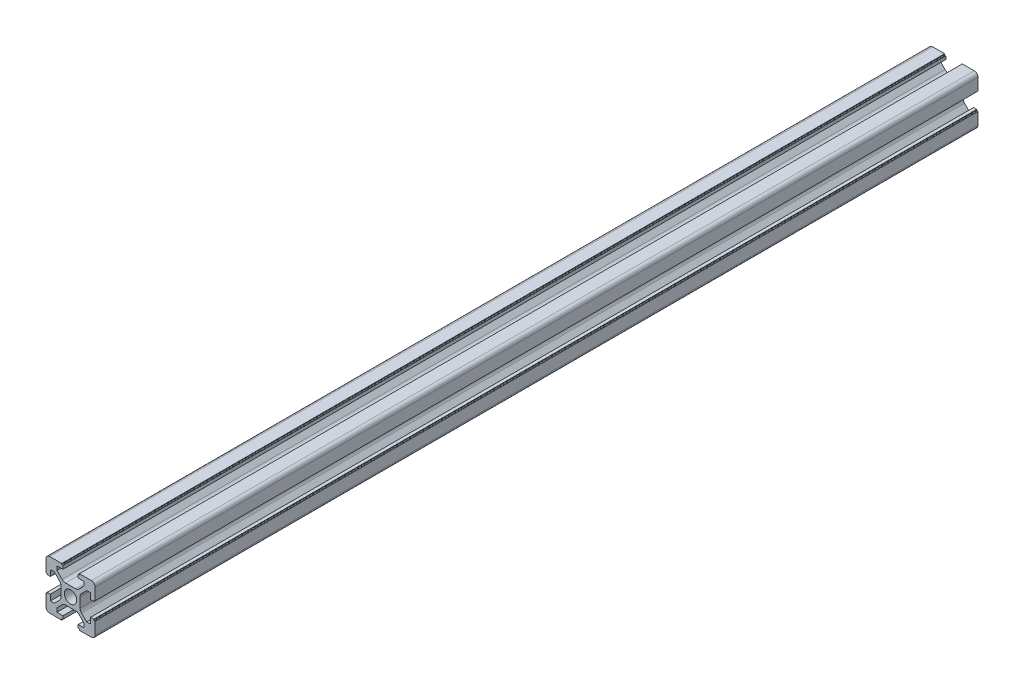
SolidWorks part; units mm, degrees
material "6063-T6"
ref_plane "Спереди" through (0, 0, 0) normal (0, 0, 1) x (1, 0, 0)
ref_plane "Сверху" through (0, 0, 0) normal (0, 1, 0) x (1, 0, 0)
ref_plane "Справа" through (0, 0, 0) normal (1, 0, 0) x (0, 0, -1)
sketch "Sketch1" plane through (0, 0, 0) normal (0, 0, 1) x (1, 0, 0)
  line L0 (0, 10) -> (0, -10) construction
  line L1 (-10, -10) -> (10, -10) construction
  line L2 (-10, -10) -> (-10, 10) construction
  line L3 (-10, 10) -> (10, 10) construction
  line L4 (10, -10) -> (10, 10) construction
  line L5 (-10, -10) -> (10, 10) construction
  line L6 (-10, 10) -> (10, -10) construction
  line L7 (-10, 0) -> (10, 0) construction
  line L8 (0, 3.9) -> (-2.0109, 3.9)
  line L9 (-3.4251, 4.4858) -> (-5.5393, 6.6)
  line L10 (-5.5393, 6.6) -> (-5.5393, 8.2)
  line L11 (-5.5393, 8.2) -> (-3.1, 8.2)
  line L12 (-3.1, 8.2) -> (-3.1, 9.5)
  line L13 (-3.1, 9.5) -> (-3.4, 9.5)
  line L14 (-3.6, 9.7) -> (-3.6, 10)
  line L15 (-3.6, 10) -> (-8.5, 10)
  line L16 (-10, 3.6) -> (-10, 8.5)
  line L17 (-9.7, 3.6) -> (-10, 3.6)
  line L18 (-9.5, 3.1) -> (-9.5, 3.4)
  line L19 (-8.2, 3.1) -> (-9.5, 3.1)
  line L20 (-8.2, 5.5393) -> (-8.2, 3.1)
  line L21 (-6.6, 5.5393) -> (-8.2, 5.5393)
  line L22 (-4.4858, 3.4251) -> (-6.6, 5.5393)
  line L23 (-3.9, 0) -> (-3.9, 2.0109)
  line L24 (3.9, 0) -> (3.9, 2.0109)
  line L25 (4.4858, 3.4251) -> (6.6, 5.5393)
  line L26 (6.6, 5.5393) -> (8.2, 5.5393)
  line L27 (8.2, 5.5393) -> (8.2, 3.1)
  line L28 (8.2, 3.1) -> (9.5, 3.1)
  line L29 (9.5, 3.1) -> (9.5, 3.4)
  line L30 (9.7, 3.6) -> (10, 3.6)
  line L31 (10, 3.6) -> (10, 8.5)
  line L32 (3.6, 10) -> (8.5, 10)
  line L33 (3.6, 9.7) -> (3.6, 10)
  line L34 (3.1, 9.5) -> (3.4, 9.5)
  line L35 (3.1, 8.2) -> (3.1, 9.5)
  line L36 (5.5393, 8.2) -> (3.1, 8.2)
  line L37 (5.5393, 6.6) -> (5.5393, 8.2)
  line L38 (3.4251, 4.4858) -> (5.5393, 6.6)
  line L39 (0, 3.9) -> (2.0109, 3.9)
  line L40 (0, -3.9) -> (2.0109, -3.9)
  line L41 (3.4251, -4.4858) -> (5.5393, -6.6)
  line L42 (5.5393, -6.6) -> (5.5393, -8.2)
  line L43 (5.5393, -8.2) -> (3.1, -8.2)
  line L44 (3.1, -8.2) -> (3.1, -9.5)
  line L45 (3.1, -9.5) -> (3.4, -9.5)
  line L46 (3.6, -9.7) -> (3.6, -10)
  line L47 (3.6, -10) -> (8.5, -10)
  line L48 (10, -3.6) -> (10, -8.5)
  line L49 (9.7, -3.6) -> (10, -3.6)
  line L50 (9.5, -3.1) -> (9.5, -3.4)
  line L51 (8.2, -3.1) -> (9.5, -3.1)
  line L52 (8.2, -5.5393) -> (8.2, -3.1)
  line L53 (6.6, -5.5393) -> (8.2, -5.5393)
  line L54 (4.4858, -3.4251) -> (6.6, -5.5393)
  line L55 (3.9, 0) -> (3.9, -2.0109)
  line L56 (-3.9, 0) -> (-3.9, -2.0109)
  line L57 (-4.4858, -3.4251) -> (-6.6, -5.5393)
  line L58 (-6.6, -5.5393) -> (-8.2, -5.5393)
  line L59 (-8.2, -5.5393) -> (-8.2, -3.1)
  line L60 (-8.2, -3.1) -> (-9.5, -3.1)
  line L61 (-9.5, -3.1) -> (-9.5, -3.4)
  line L62 (-9.7, -3.6) -> (-10, -3.6)
  line L63 (-10, -3.6) -> (-10, -8.5)
  line L64 (-3.6, -10) -> (-8.5, -10)
  line L65 (-3.6, -9.7) -> (-3.6, -10)
  line L66 (-3.1, -9.5) -> (-3.4, -9.5)
  line L67 (-3.1, -8.2) -> (-3.1, -9.5)
  line L68 (-5.5393, -8.2) -> (-3.1, -8.2)
  line L69 (-5.5393, -6.6) -> (-5.5393, -8.2)
  line L70 (-3.4251, -4.4858) -> (-5.5393, -6.6)
  line L71 (0, -3.9) -> (-2.0109, -3.9)
  circle A0 centre (0, 0) radius 2.5
  arc A1 (-8.5, 10) -> (-10, 8.5) centre (-8.5, 8.5) ccw
  arc A2 (-2.0109, 3.9) -> (-3.4251, 4.4858) centre (-2.0109, 5.9) cw
  arc A3 (-3.4, 9.5) -> (-3.6, 9.7) centre (-3.4, 9.7) cw
  arc A4 (-9.5, 3.4) -> (-9.7, 3.6) centre (-9.7, 3.4) ccw
  arc A5 (-3.9, 2.0109) -> (-4.4858, 3.4251) centre (-5.9, 2.0109) ccw
  arc A6 (10, 8.5) -> (8.5, 10) centre (8.5, 8.5) ccw
  arc A7 (3.9, 2.0109) -> (4.4858, 3.4251) centre (5.9, 2.0109) cw
  arc A8 (9.5, 3.4) -> (9.7, 3.6) centre (9.7, 3.4) cw
  arc A9 (3.4, 9.5) -> (3.6, 9.7) centre (3.4, 9.7) ccw
  arc A10 (2.0109, 3.9) -> (3.4251, 4.4858) centre (2.0109, 5.9) ccw
  arc A11 (8.5, -10) -> (10, -8.5) centre (8.5, -8.5) ccw
  arc A12 (2.0109, -3.9) -> (3.4251, -4.4858) centre (2.0109, -5.9) cw
  arc A13 (3.4, -9.5) -> (3.6, -9.7) centre (3.4, -9.7) cw
  arc A14 (9.5, -3.4) -> (9.7, -3.6) centre (9.7, -3.4) ccw
  arc A15 (3.9, -2.0109) -> (4.4858, -3.4251) centre (5.9, -2.0109) ccw
  arc A16 (-10, -8.5) -> (-8.5, -10) centre (-8.5, -8.5) ccw
  arc A17 (-3.9, -2.0109) -> (-4.4858, -3.4251) centre (-5.9, -2.0109) cw
  arc A18 (-9.5, -3.4) -> (-9.7, -3.6) centre (-9.7, -3.4) cw
  arc A19 (-3.4, -9.5) -> (-3.6, -9.7) centre (-3.4, -9.7) ccw
  arc A20 (-2.0109, -3.9) -> (-3.4251, -4.4858) centre (-2.0109, -5.9) ccw
  point P0 (0, 0)
  point P42 (0, 0)
  point P70 (0, 0)
  point P98 (0, 0)
  point P126 (0, 0)
  dimension "D3" = 5
  dimension "D4" = 3
  dimension "D12" = 2
  dimension "D13" = 0.2
  dimension "D1" = 20
  dimension "D2" = 20
  dimension "D5" = 6.2
  dimension "D6" = 7.2
  dimension "D7" = 1.8
  dimension "D8" = 0.5
  dimension "D9" = 3.4
  dimension "D10" = 1.5
  dimension "D11" = 6.1
  dimension "D14" = 4
extrude "Extrude1" add sketch "Sketch1" along normal blind 360
